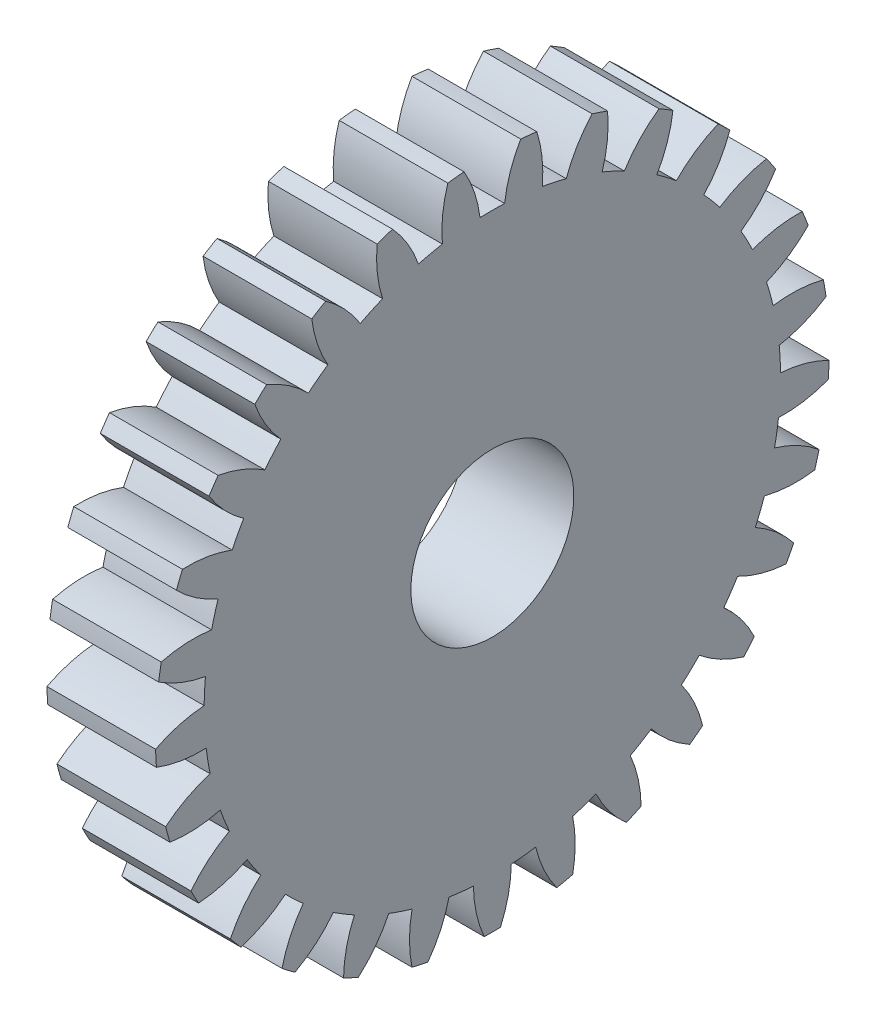
SolidWorks part; units mm, degrees
ref_plane "Plane1" through (0, 0, 0) normal (0, 0, 1) x (1, 0, 0)
ref_plane "Plane2" through (0, 0, 0) normal (0, 1, 0) x (1, 0, 0)
ref_plane "Plane3" through (0, 0, 0) normal (1, 0, 0) x (0, 0, -1)
sketch "HoldingSke" plane through (0, 0, 0) normal (0, 1, 0) x (1, 0, 0)
  line L0 (0, 0) -> (444.3068, -246.2833)
  line L1 (-15, 0) -> (100, 0) construction
  line L2 (0, 0) -> (-2.1039, 2.3779)
  line L3 (0, 0) -> (-11.863, 4.5341)
  line L4 (0, 0) -> (7.5532, 4.1868)
  line L5 (0, 0) -> (-47.5972, -17.7524)
  line L6 (0, 0) -> (-5.2639, -3.5516)
  line L7 (-2.1039, 2.3779) -> (8.8308, 51.9871)
  line L8 (-76.2, 54.61) -> (-65.4837, 54.61)
  line L9 (-67.7845, 28.3722) -> (-49.3413, 33.142)
  line L10 (-76.2, 71.12) -> (104.1128, 71.12)
  line L11 (0, 0) -> (-6.35, 0)
  line L12 (-76.2, 101.6) -> (-76.1492, 101.6)
  line L13 (24.9733, 27.94) -> (52.9518, 28.4284)
  line L14 (24.9733, 27.94) -> (25.0241, 27.9398)
  line L15 (24.9733, 27.94) -> (100.4021, 29.52)
  circle A0 centre (0, 0) radius 4.7625
  circle A1 centre (0, 0) radius 16.8402
  circle A2 centre (0, 0) radius 38.1
  circle A3 centre (0, 0) radius 4.7625
  dimension "Hub_dia" = 76.2
  dimension "Bore" = 9.525
  dimension "MBD" = 9.525
  dimension "Pitch" = 508
  dimension "Overall_len" = 50.8
  dimension "Thickness" = 6.35
  dimension "OAL" = 50.8001
  dimension "T_dim" = 10.7163
  dimension "Ap" = 14.5
  dimension "H" = 19.05
  dimension "Pitch_radius" = 180.3128
  dimension "Width" = 6.35
  dimension "Backlash" = 0.0508
  dimension "Addendum_fac" = 1
  dimension "Dedendum_fac" = 1.2
  dimension "Clearance_fac" = 0.2
  dimension "Dedendum_add" = 0.0508
sketch "BasProSke" plane through (0, 0, 0) normal (0, 1, 0) x (1, 0, 0)
  line L0 (-10, 0) -> (60, 0) construction
  line L1 (0, 0) -> (0, 19.685)
  line L2 (0, 0) -> (6.35, 0)
  line L3 (6.35, 0) -> (6.35, 19.685)
  line L4 (6.35, 19.685) -> (0, 19.685)
  dimension "Thickness" = 6.35
  dimension "Diameter" = 39.37
revolve "Base-Revolve" add sketch "BasProSke" angle 360 about L0
sketch "TooCutSke" plane through (0, 0, 0) normal (1, 0, 0) x (0, 0, -1)
  line L1 (0, 0) -> (0, 107) construction
  line L2 (0, 0) -> (-1.0858, 18.383) construction
  line L3 (0, 0) -> (-3.9772, 36.5696) construction
  line L4 (-1.0858, 18.383) -> (-1.9886, 18.2848) construction
  arc A0 (0.7174, 16.8249) -> (-0.7174, 16.8249) centre (0, 0) ccw
  arc A1 (1.6702, 19.6395) -> (-1.6702, 19.6395) centre (0, 0) ccw
  circle A2 centre (0, 0) radius 18.415 construction
  circle A3 centre (0, 0) radius 17.8284 construction
  arc A4 (-0.7174, 16.8249) -> (-1.6702, 19.6395) centre (-8.0275, 15.9189) ccw
  arc A5 (1.6702, 19.6395) -> (0.7174, 16.8249) centre (8.0275, 15.9189) ccw
  dimension "Pitch_dia" = 36.83
  dimension "Half_CT" = 0.9081
extrude "ToothCut" cut sketch "TooCutSke" along normal through all
fillet "Breaks" [suppressed] radius 0.0254
fillet "RootFillets" [suppressed] radius 0.3048
pattern_circular "TeethCuts" count 29 every 12.414 about axis through (-10, 0, 0) along (1, 0, 0) of "ToothCut", "RootFillets", "Breaks"
sketch "HubNeaOneSke" plane through (0, 0, 0) normal (-1, 0, 0) x (0, 0, 1)
  circle A0 centre (0, 0) radius 16.8402
extrude "HubNearOne" [suppressed] add sketch "HubNeaOneSke" along normal blind 44.4501
sketch "HubNeaBotSke" plane through (0, 0, 0) normal (-1, 0, 0) x (0, 0, 1)
  circle A0 centre (0, 0) radius 16.8402
extrude "HubNearBoth" [suppressed] add sketch "HubNeaBotSke" along normal blind 22.225
ref_plane "FarPln" through (6.35, 0, 0) normal (1, 0, 0) x (0, 0, -1)
sketch "HubFarSke" plane through (6.35, 0, 0) normal (1, 0, 0) x (0, 0, -1)
  circle A0 centre (0, 0) radius 16.8402
extrude "HubFar" [suppressed] add sketch "HubFarSke" along normal blind 22.225
sketch "BorSke" plane through (0, 0, 0) normal (1, 0, 0) x (0, 0, -1)
  circle A0 centre (0, 0) radius 4.7625
  dimension "Diameter" = 9.525
extrude "Bore" cut sketch "BorSke" along normal mid plane 101.6001
sketch "KeySke" plane through (0, 0, 0) normal (1, 0, 0) x (0, 0, -1)
  line L0 (-1.1913, 0) -> (-1.1913, 5.9538)
  line L1 (-1.1913, 5.9538) -> (1.1913, 5.9538)
  line L2 (1.1913, 5.9538) -> (1.1913, 0)
  line L3 (0, 0) -> (0, 34) construction
  line L4 (-1.1913, 0) -> (1.1913, 0)
  dimension "Offset" = 5.9538
  dimension "Width" = 2.3825
extrude "Keyway" [suppressed] cut sketch "KeySke" along normal mid plane 101.6001
pattern_circular "Keyway2" [suppressed] count 2 every 90 about axis through (-10, 0, 0) along (1, 0, 0)
equation "' \"Pitch@HoldingSke\" = 4"
equation "' \"Num_teeth@HoldingSke\" = 12"
equation "' \"Ap@HoldingSke\" =  20"
equation "' \"Ap@HoldingSke\" = 20"
equation "' \"Width@HoldingSke\" = 0.5"
equation "' \"Hub_dia@HoldingSke\"= 1"
equation "' \"Hub_dia@HoldingSke\" = 1"
equation "' \"Overall_len@HoldingSke\" = 1.0"
equation "' \"Bore@HoldingSke\" = 0.75"
equation "' \"T_dim@HoldingSke\" = 0.85"
equation "' \"Width@KeySke\" = 0.25"
equation "' \"Show_teeth@HoldingSke\" = 13"
equation "' \"Backlash@HoldingSke\" = 0.009"
equation "' \"Addendum_fac@HoldingSke\" = 1.0"
equation "' \"Dedendum_fac@HoldingSke\" = 1.25"
equation "' \"Dedendum_add@HoldingSke\" = 0.00005"
equation "' \"Clearance_fac@HoldingSke\" = 0.25"
equation "' \"Pitch@HoldingSke\" = 0.5"
equation "' \"Num_teeth@HoldingSke\" = 23"
equation "' \"Show_teeth@HoldingSke\" = 23"
equation "' \"Backlash@HoldingSke\" = 0.0375"
equation "\"Overcut_dia@TooCutSke\" = (\"Num_teeth@HoldingSke\" + 2 * \"Addendum_fac@HoldingSke\") / \"Pitch@HoldingSke\" + 0.002"
equation "\"Pitch_dia@TooCutSke\" = \"Num_teeth@HoldingSke\" / \"Pitch@HoldingSke\""
equation "\"Base_dia@TooCutSke\" = \"Num_teeth@HoldingSke\" / \"Pitch@HoldingSke\" * cos((\"Ap@HoldingSke\"  * 3.14159265 / 180))"
equation "\"Root_dia@TooCutSke\" = (\"Num_teeth@HoldingSke\" + 2) / \"Pitch@HoldingSke\" - 2 * (\"Addendum_fac@HoldingSke\" + \"Dedendum_fac@HoldingSke\") / \"Pitch@HoldingSke\" - \"Dedendum_add@HoldingSke\" * 2"
equation "\"Half_ang@TooCutSke\" = 180 / \"Num_teeth@HoldingSke\""
equation "\"Half_CT@TooCutSke\" = \"Num_teeth@HoldingSke\" / \"Pitch@HoldingSke\" * sin((3.14159265 / 2 / \"Num_teeth@HoldingSke\")) / 2 - 7 * \"Backlash@HoldingSke\" / 4"
equation "\"Flank_rad@TooCutSke\" = \"Num_teeth@HoldingSke\" / \"Pitch@HoldingSke\" / 5"
equation "\"Radius@RootFillets\" = \"Clearance_fac@HoldingSke\" / \"Pitch@HoldingSke\" + \"Dedendum_add@HoldingSke\""
equation "\"Break_rad@Breaks\" = 0.02 / \"Pitch@HoldingSke\""
equation "\"Thickness@HoldingSke\" = \"Width@HoldingSke\""
equation "\"OAL@HoldingSke\" = \"Thickness@HoldingSke\""
equation "\"MHD@HoldingSke\" = (\"Num_teeth@HoldingSke\" + 2) / \"Pitch@HoldingSke\" - 2 * (\"Addendum_fac@HoldingSke\" + \"Dedendum_fac@HoldingSke\")  / \"Pitch@HoldingSke\" - \"Dedendum_add@HoldingSke\" * 2"
equation "\"MBD@HoldingSke\" = (\"Num_teeth@HoldingSke\" + 2) / \"Pitch@HoldingSke\" - 2 * (\"Addendum_fac@HoldingSke\" + \"Dedendum_fac@HoldingSke\")  / \"Pitch@HoldingSke\" - \"Dedendum_add@HoldingSke\" * 2 - 0.002"
equation "\"MHD@HoldingSke\" = ((sgn( \"MHD@HoldingSke\" - \"Hub_dia@HoldingSke\" )-1)*( \"MHD@HoldingSke\" - \"Hub_dia@HoldingSke\" ))/-2+ \"Hub_dia@HoldingSke\""
equation "\"MBD@HoldingSke\" = ((sgn( \"MBD@HoldingSke\" - \"Bore@HoldingSke\" )-1)*( \"MBD@HoldingSke\" - \"Bore@HoldingSke\" ))/-2+ \"Bore@HoldingSke\""
equation "\"OAL@HoldingSke\" = ((sgn( \"OAL@HoldingSke\" - \"Overall_len@HoldingSke\" )+1)*( \"OAL@HoldingSke\" - \"Overall_len@HoldingSke\" ))/2 + \"Overall_len@HoldingSke\" + 0.000002"
equation "\"Num_teeth@TeethCuts\" = int( \"Show_teeth@HoldingSke\" ) + 1"
equation "\"Num_teeth@TeethCuts\" = ((sgn( \"Num_teeth@TeethCuts\" - \"Num_teeth@HoldingSke\" )-1)*( \"Num_teeth@TeethCuts\" - \"Num_teeth@HoldingSke\" ))/-2+ \"Num_teeth@HoldingSke\""
equation "\"Num_teeth@TeethCuts\" = ((sgn( \"Num_teeth@TeethCuts\" - 2.0)+1)*( \"Num_teeth@TeethCuts\" - 2.0))/2 +2.0"
equation "\"Angle@TeethCuts\" = 360.0 / \"Num_teeth@HoldingSke\""
equation "\"Diameter@BasProSke\" = (\"Num_teeth@HoldingSke\" + 2 * \"Addendum_fac@HoldingSke\") / \"Pitch@HoldingSke\""
equation "\"Thickness@BasProSke\"  = \"Thickness@HoldingSke\""
equation "' \"Fillet_rad@BasProSke\" =  \"Thickness@HoldingSke\" * 0.05"
equation "' \"Fillet_rad@BasProSke\" = \"Thickness@HoldingSke\" * 0.05"
equation "\"MHD@HoldingSke\" = ((sgn( \"MHD@HoldingSke\" - \"Root_dia@TooCutSke\" )-1)*( \"MHD@HoldingSke\" - \"Root_dia@TooCutSke\" ))/-2+ \"Root_dia@TooCutSke\""
equation "\"Diameter@HubNeaOneSke\" = \"MHD@HoldingSke\""
equation "\"Length@HubNearOne\" = \"OAL@HoldingSke\" - \"Thickness@BasProSke\""
equation "\"Diameter@HubNeaBotSke\" = \"MHD@HoldingSke\""
equation "\"Length@HubNearBoth\" = ( \"OAL@HoldingSke\" - \"Thickness@BasProSke\" ) / 2.0"
equation "\"Thickness@FarPln\" = \"Thickness@BasProSke\""
equation "\"Diameter@HubFarSke\" = \"MHD@HoldingSke\""
equation "\"Length@HubFar\" = ( \"OAL@HoldingSke\" - \"Thickness@BasProSke\" ) / 2.0"
equation "\"Diameter@BorSke\" = \"MBD@HoldingSke\""
equation "\"D1@Bore\" = \"OAL@HoldingSke\" * 2.0"
equation "\"D1@Keyway\" = \"OAL@HoldingSke\" * 2.0"
equation "\"Offset@KeySke\" = \"T_dim@HoldingSke\" - \"MBD@HoldingSke\" / 2.0"
